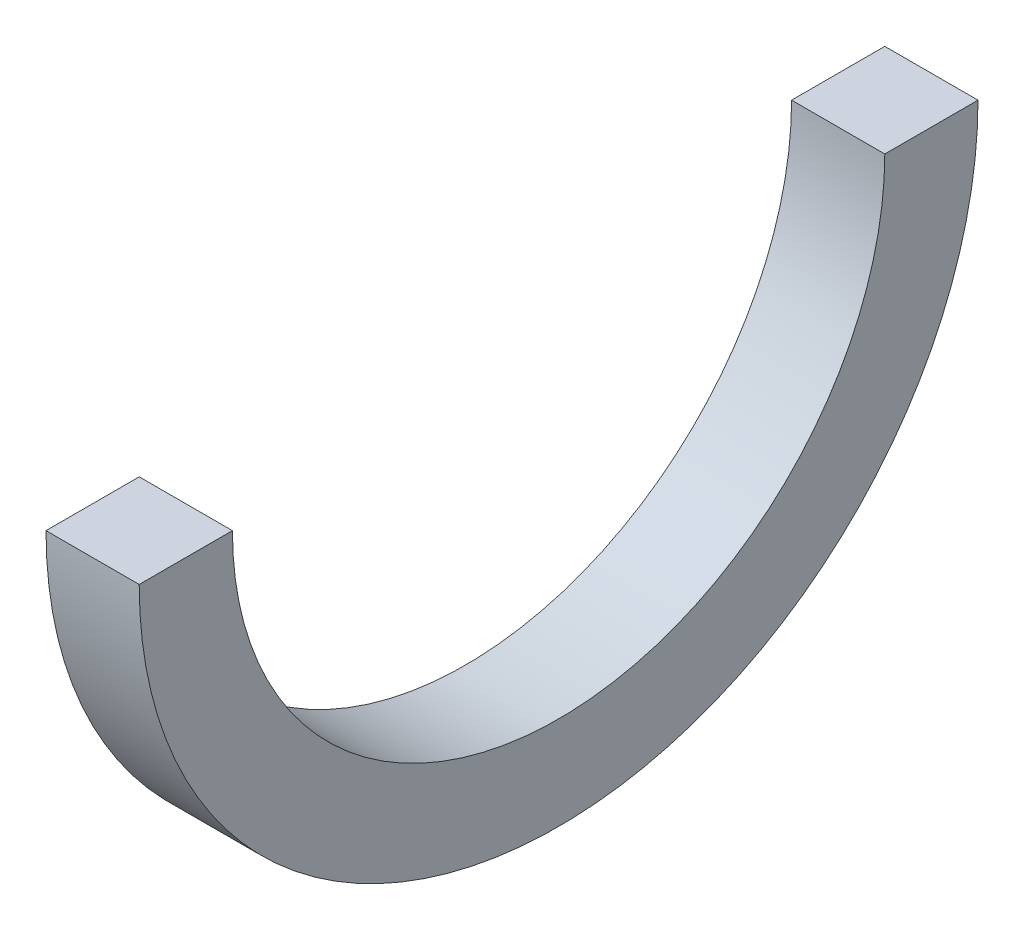
SolidWorks part; units mm, degrees
ref_plane "Front Plane" through (0, 0, 0) normal (0, 0, 1) x (1, 0, 0)
ref_plane "Top Plane" through (0, 0, 0) normal (0, 1, 0) x (1, 0, 0)
ref_plane "Right Plane" through (0, 0, 0) normal (1, 0, 0) x (0, 0, -1)
sketch "Sketch1" plane through (0, 0, 0) normal (1, 0, 0) x (0, 0, -1)
  line L0 (-50.9719, 0) -> (17.5, 0) construction
  line L10 (0, 14.7129) -> (0, -11.3151) construction
  line L14 (22.5, 0) -> (41.648, 0) construction
  line L15 (-22.5, 0) -> (-17.5, 0)
  line L16 (17.5, 0) -> (22.5, 0)
  arc A0 (-17.5, 0) -> (17.5, 0) centre (0, 0) ccw
  arc A1 (-22.5, 0) -> (22.5, 0) centre (0, 0) ccw
  dimension "D1" = 17.5
  dimension "D2" = 5
extrude "Boss-Extrude1" add sketch "Sketch1" along normal mid plane 5
